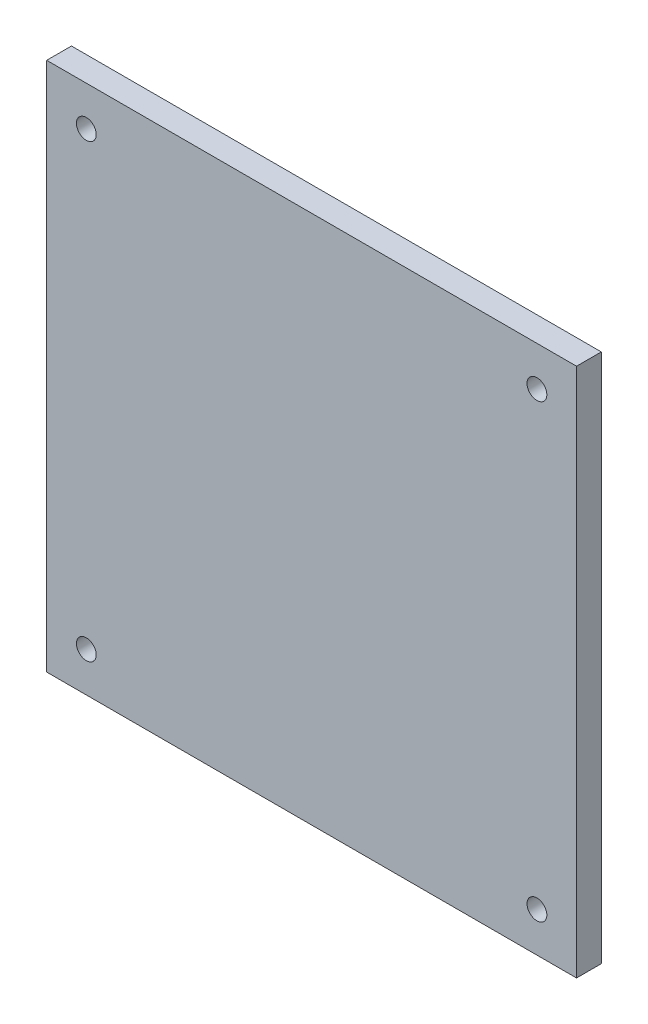
SolidWorks part; units mm, degrees
ref_plane "Front Plane" through (0, 0, 0) normal (0, 0, 1) x (1, 0, 0)
ref_plane "Top Plane" through (0, 0, 0) normal (0, 1, 0) x (1, 0, 0)
ref_plane "Right Plane" through (0, 0, 0) normal (1, 0, 0) x (0, 0, -1)
sketch "Sketch1" plane through (0, 0, 0) normal (0, 0, 1) x (1, 0, 0)
  line L1 (-53.5, 53.5) -> (53.5, 53.5)
  line L2 (-53.5, 53.5) -> (-53.5, -53.5)
  line L3 (-53.5, -53.5) -> (53.5, -53.5)
  line L4 (53.5, 53.5) -> (53.5, -53.5)
  line L5 (-53.5, 53.5) -> (53.5, -53.5) construction
  line L6 (-53.5, -53.5) -> (53.5, 53.5) construction
  point P0 (0, 0)
  dimension "D1" = 107
extrude "Boss-Extrude1" add sketch "Sketch1" along normal blind 5
sketch "Sketch2" plane through (0, 0, 5) normal (0, 0, 1) x (1, 0, 0)
  line L0 (-53.5, 0) -> (53.5, 0) construction
  line L1 (-53.5, 53.5) -> (-53.5, -53.5) construction
  line L2 (53.5, -53.5) -> (53.5, 53.5) construction
  line L3 (0, 53.5) -> (0, -53.5) construction
  line L4 (53.5, 53.5) -> (-53.5, 53.5) construction
  line L5 (-53.5, -53.5) -> (53.5, -53.5) construction
  line L6 (-53.5, 53.5) -> (-45.5, 53.5) construction
  line L7 (-45.5, 53.5) -> (-45.5, 45.5) construction
  circle A0 centre (-45.5, 45.5) radius 2
  circle A1 centre (-45.5, -45.5) radius 2
  circle A2 centre (45.5, -45.5) radius 2
  circle A3 centre (45.5, 45.5) radius 2
  dimension "D3" = 4
  dimension "D1" = 8
  dimension "D2" = 8
extrude "Cut-Extrude1" cut sketch "Sketch2" against normal blind 5
